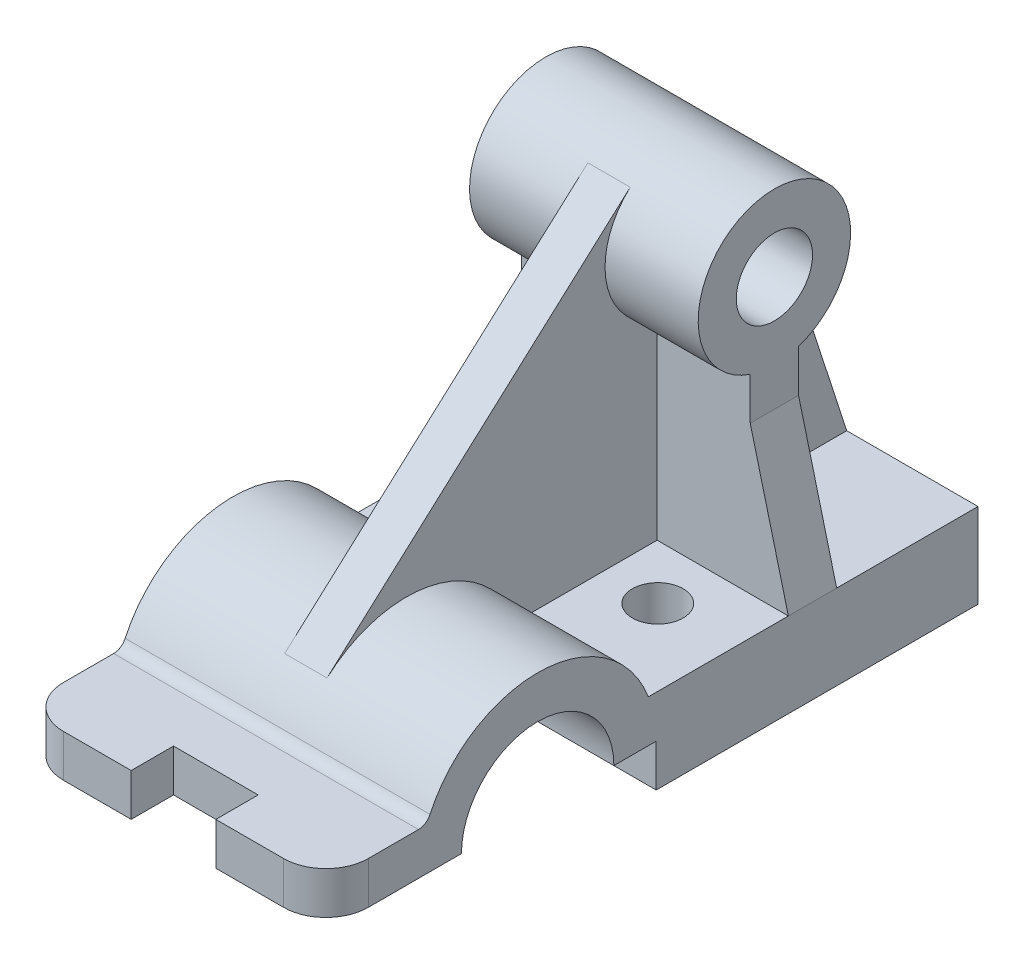
SolidWorks part; units mm, degrees
ref_plane "Front Plane" through (0, 0, 0) normal (0, 0, 1) x (1, 0, 0)
ref_plane "Top Plane" through (0, 0, 0) normal (0, 1, 0) x (1, 0, 0)
ref_plane "Right Plane" through (0, 0, 0) normal (1, 0, 0) x (0, 0, -1)
sketch "Sketch1" plane through (0, 0, 0) normal (0, 1, 0) x (1, 0, 0)
  line L1 (-26, -77) -> (26, -77)
  line L2 (-36, -67) -> (-36, 77)
  line L3 (-36, 77) -> (36, 77)
  line L4 (36, -67) -> (36, 77)
  line L5 (-36, -77) -> (36, 77) construction
  line L6 (-36, 77) -> (36, -77) construction
  arc A0 (36, -67) -> (26, -77) centre (26, -67) cw
  arc A1 (-26, -77) -> (-36, -67) centre (-26, -67) cw
  point P0 (0, 0)
  dimension "D3" = 10
  dimension "D1" = 154
  dimension "D2" = 72
extrude "Boss-Extrude1" add sketch "Sketch1" along normal blind 20
sketch "Sketch3" plane through (-36, 0, 0) normal (-1, 0, 0) x (0, 0, 1)
  line L0 (-77, 0) -> (67, 0) construction
  line L1 (-1, 0) -> (77, 0)
  line L2 (-1, 0) -> (-1, 10)
  line L3 (-1, 10) -> (77, 10)
  line L4 (77, 0) -> (77, 10)
  line L5 (77, 20) -> (77, 0) construction
  dimension "D1" = 78
extrude "Cut-Extrude1" cut sketch "Sketch3" against normal through all
sketch "Sketch5" plane through (0, 20, 0) normal (0, 1, 0) x (1, 0, 0)
  line L0 (-26, -77) -> (26, -77) construction
  line L1 (-10, -77) -> (10, -77)
  line L2 (-10, -77) -> (-10, -67)
  line L3 (-10, -67) -> (10, -67)
  line L4 (10, -77) -> (10, -67)
  point P6 (0, -67)
  dimension "D1" = 20
  dimension "D2" = 10
extrude "Cut-Extrude2" cut sketch "Sketch5" against normal through all
sketch "Sketch9" plane through (-36, 0, 0) normal (-1, 0, 0) x (0, 0, 1)
  line L0 (67, 10) -> (-1, 10) construction
  line L1 (-1, 10) -> (55, 10)
  line L2 (0.8466, 20) -> (12.0334, 20)
  line L3 (-77, 20) -> (67, 20) construction
  line L4 (53.1534, 20) -> (67, 20)
  arc A0 (45, 10) -> (9, 10) centre (27, 10) ccw
  arc A1 (55, 10) -> (53.1534, 20) centre (27, 10) ccw
  arc A2 (52.419, 21.7419) -> (55.1425, 20) centre (55.1425, 23) ccw
  arc A3 (52.419, 21.7419) -> (-1, 10) centre (27, 10) ccw
  line M4 (-1, 10) -> (67, 10)
  line M6 (67, 20) -> (-77, 20)
  dimension "D1" = 56
  dimension "D2" = 36
  dimension "D3" = 6
extrude "Boss-Extrude3" add sketch "Sketch9" against normal through all contours A2 A3 A0 L4 M6 | A1 A0 M4 M6 | A3 A0 M6 M4
sketch "Sketch10" plane through (-36, 0, 0) normal (-1, 0, 0) x (0, 0, 1)
  circle A0 centre (27, 10) radius 18
extrude "Cut-Extrude4" cut sketch "Sketch10" against normal through all
sketch "Sketch11" plane through (0, 20, 0) normal (0, 1, 0) x (1, 0, 0)
  line L0 (-36, 77) -> (-36, -0.8466) construction
  line L1 (-36, -0.8466) -> (-36, -52.419) construction
  circle A0 centre (-18, 19.3672) radius 6
  point P6 (-36, -26.6328)
  dimension "D1" = 12
  dimension "D2" = 18
  dimension "D3" = 46
extrude "Cut-Extrude5" cut sketch "Sketch11" against normal through all
mirror "Mirror1" about plane through (0, 0, 0) normal (1, 0, 0) of "Cut-Extrude5"
sketch "Sketch14" plane through (-36, 0, 0) normal (-1, 0, 0) x (0, 0, 1)
  line L0 (-77, 0) -> (-1, 0) construction
  circle A0 centre (-37.9146, 82) radius 18
  circle A1 centre (-37.9146, 82) radius 9
  dimension "D1" = 36
  dimension "D2" = 18
  dimension "D3" = 82
extrude "Boss-Extrude4" add sketch "Sketch14" against normal through all separate body
sketch "Sketch19" plane through (-36, 0, 0) normal (-1, 0, 0) x (0, 0, 1)
  circle A0 centre (-37.9146, 82) radius 18
extrude "Cut-Extrude6" cut sketch "Sketch19" against normal blind 9
mirror "Mirror2" about plane through (0, 0, 0) normal (1, 0, 0) of "Cut-Extrude6"
sketch "Sketch21" plane through (-27, 0, 0) normal (-1, 0, 0) x (0, 0, 1)
  line L1 (-32.2099, 19.9279) -> (-43.6193, 19.9279)
  line L2 (-32.2099, 19.9279) -> (-32.2099, 64.9279)
  line L4 (-43.6193, 19.9279) -> (-43.6193, 64.9279)
  circle A0 centre (-37.9146, 82) radius 18 construction
  arc A1 (-43.6193, 64.9279) -> (-32.2099, 64.9279) centre (-37.9146, 82) ccw
  point P0 (-37.9146, 64)
  dimension "D1" = 45
extrude "Boss-Extrude5" add sketch "Sketch21" against normal through all and the other way up to vertex (9 mm away)
sketch "Sketch24" plane through (0, 0, -43.6193) normal (0, 0, -1) x (-1, 0, 0)
  line L0 (-27, 64.9279) -> (-27, 54.9279)
  line L1 (-27, 54.9279) -> (-36, 20)
  line L2 (27, 64.9279) -> (27, 54.9279)
  line L3 (27, 54.9279) -> (36, 20)
  line L4 (-27, 64.9279) -> (-36, 64.9279)
  line L5 (-36, 64.9279) -> (-36, 20)
  line L6 (27, 64.9279) -> (36, 64.9279)
  line L7 (36, 64.9279) -> (36, 20)
  dimension "D1" = 10
  dimension "D2" = 10
extrude "Cut-Extrude8" cut sketch "Sketch24" against normal up to next (42.6193 mm away)
sketch "Sketch30" plane through (0, 0, 0) normal (1, 0, 0) x (0, 0, -1)
  line L0 (-45.7508, 30.7944) -> (25.8605, 95.3679)
  line L1 (-0.8466, 20) -> (32.2099, 20)
  line L2 (32.2099, 20) -> (32.2099, 64.9279)
  arc A0 (25.8605, 95.3679) -> (32.2099, 64.9279) centre (37.9146, 82) ccw
  arc A1 (-0.8466, 20) -> (-45.7508, 30.7944) centre (-27, 10) ccw
  arc A2 (43.6193, 64.9279) -> (32.2099, 64.9279) centre (37.9146, 82) ccw construction
  point P7 (0, 0)
extrude "Boss-Extrude6" add sketch "Sketch30" along normal mid plane 10
sketch "Sketch31" plane through (0, 0, 0) normal (1, 0, 0) x (0, 0, -1)
  line L1 (43.6193, 64.9279) -> (43.6193, 20)
  line L2 (43.6193, 20) -> (77, 20) construction
  line L3 (43.6193, 20) -> (77, 20)
  line L4 (55.0326, 87.5655) -> (77, 20)
  arc A0 (43.6193, 64.9279) -> (32.2099, 64.9279) centre (37.9146, 82) ccw construction
  arc A1 (43.6193, 64.9279) -> (55.0326, 87.5655) centre (37.9146, 82) ccw
extrude "Boss-Extrude7" add sketch "Sketch31" along normal mid plane 10
